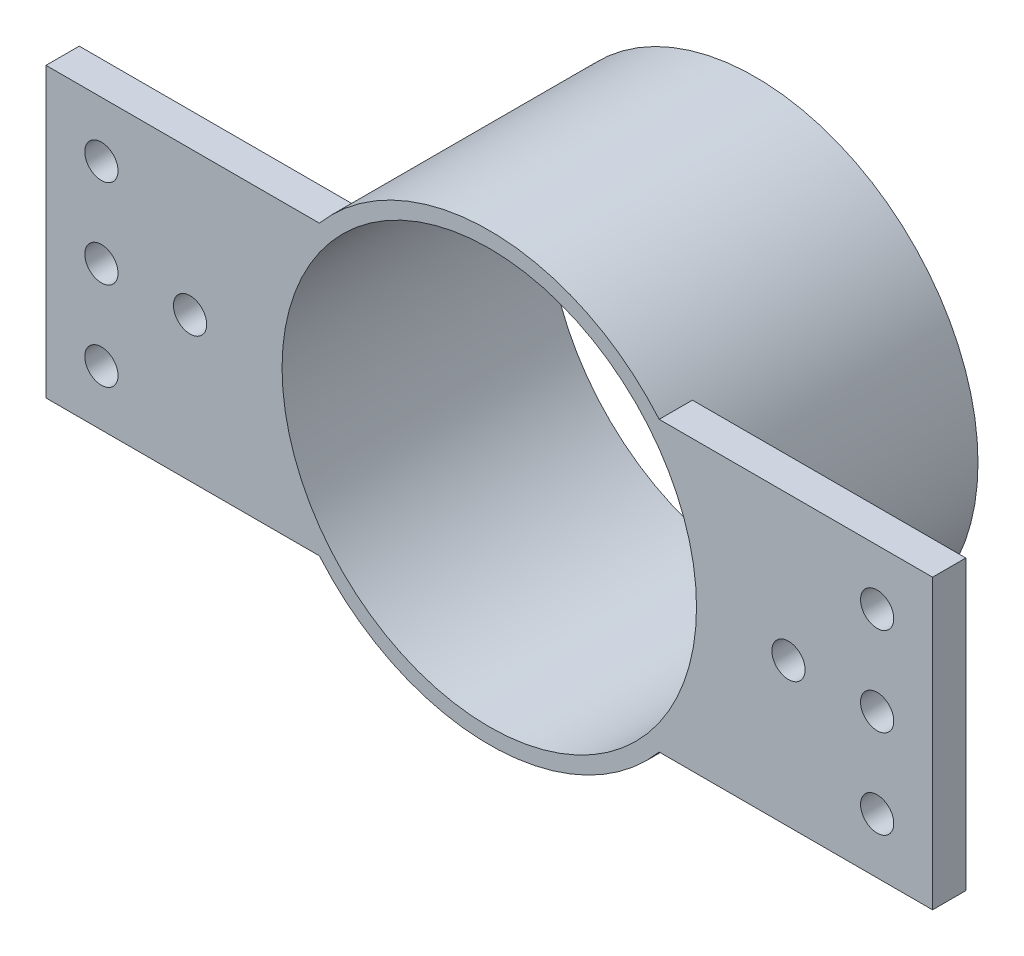
SolidWorks part; units mm, degrees
ref_plane "前视基准面" through (0, 0, 0) normal (0, 0, 1) x (1, 0, 0)
ref_plane "上视基准面" through (0, 0, 0) normal (0, 1, 0) x (1, 0, 0)
ref_plane "右视基准面" through (0, 0, 0) normal (1, 0, 0) x (0, 0, -1)
sketch "草图1" plane through (0, 0, 0) normal (0, 0, 1) x (1, 0, 0)
  line L1 (-40, 13) -> (40, 13)
  line L2 (-40, 13) -> (-40, -13)
  line L3 (-40, -13) -> (40, -13)
  line L4 (40, 13) -> (40, -13)
  line L5 (-40, 13) -> (40, -13) construction
  line L6 (-40, -13) -> (40, 13) construction
  circle A0 centre (-35, 0) radius 1.5
  circle A1 centre (-27, 0) radius 1.5
  circle A2 centre (-35, 8) radius 1.5
  circle A3 centre (-35, -8) radius 1.5
  circle A4 centre (35, -8) radius 1.5
  circle A5 centre (35, 8) radius 1.5
  circle A6 centre (35, 0) radius 1.5
  circle A7 centre (27, 0) radius 1.5
  point P0 (0, 0)
  dimension "D3" = 5
  dimension "D1" = 80
  dimension "D2" = 26
  dimension "D6" = 8
extrude "凸台-拉伸1" add sketch "草图1" along normal blind 3
sketch "草图2" plane through (0, 0, 3) normal (0, 0, 1) x (1, 0, 0)
  circle A0 centre (0, 0) radius 20.1
  dimension "D1" = 40.2
extrude "凸台-拉伸2" add sketch "草图2" against normal blind 24
sketch "草图3" plane through (0, 0, -21) normal (0, 0, -1) x (-1, 0, 0)
  circle A0 centre (0, 0) radius 18.7
  dimension "D1" = 37.4
extrude "切除-拉伸1" cut sketch "草图3" against normal blind 25
